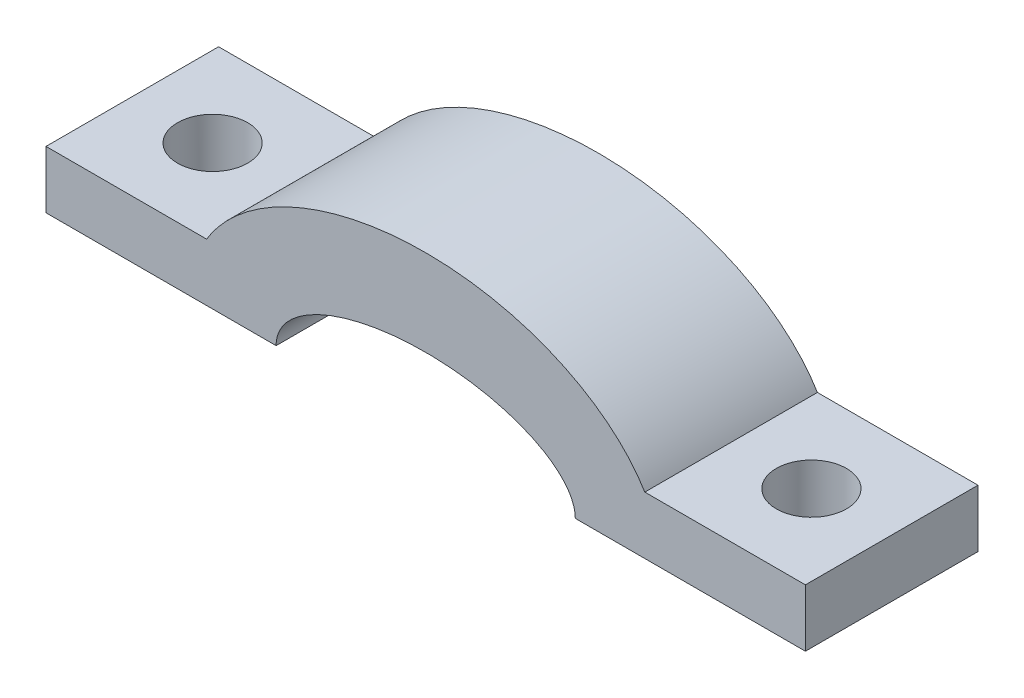
SolidWorks part; units mm, degrees
ref_plane "Front Plane" through (0, 0, 0) normal (0, 0, 1) x (1, 0, 0)
ref_plane "Top Plane" through (0, 0, 0) normal (0, 1, 0) x (1, 0, 0)
ref_plane "Right Plane" through (0, 0, 0) normal (1, 0, 0) x (0, 0, -1)
sketch "Sketch2" plane through (0, 0, 0) normal (0, 0, 1) x (1, 0, 0)
  line L0 (-20.5, 0) -> (20.5, 0)
  ellipse E0 centre (0, 0) end of major axis (13, 0) minor radius 6
  ellipse E1 centre (0, 0) end of major axis (20.5, 0) minor radius 13.5
  dimension "D1" = 26
  dimension "D2" = 12
  dimension "D3" = 41
  dimension "D4" = 27
extrude "Boss-Extrude1" add sketch "Sketch2" along normal blind 15 contours L0 E1 E0
sketch "Sketch3" plane through (0, 0, 0) normal (0, -1, 0) x (1, 0, 0)
  line L1 (13, 15) -> (33, 15)
  line L2 (13, 15) -> (13, 0)
  line L3 (13, 0) -> (33, 0)
  line L4 (33, 15) -> (33, 0)
  line L5 (-13, 15) -> (-33, 15)
  line L6 (-13, 15) -> (-13, 0)
  line L7 (-13, 0) -> (-33, 0)
  line L8 (-33, 15) -> (-33, 0)
  dimension "D1" = 20
extrude "Boss-Extrude2" add sketch "Sketch3" against normal blind 5
sketch "Sketch5" plane through (0, 5, 0) normal (0, 1, 0) x (1, 0, 0)
  line L0 (19.0421, 0) -> (33, -15) construction
  line L1 (19.0421, -15) -> (33, 0) construction
  line L2 (0, 0) -> (0, -15) construction
  line L3 (-19.0421, -15) -> (19.0421, -15) construction
  circle A0 centre (26.0211, -7.5) radius 3.05
  circle A1 centre (-26.0211, -7.5) radius 3.05
  dimension "D1" = 6.1
extrude "Cut-Extrude2" cut sketch "Sketch5" against normal blind 10
